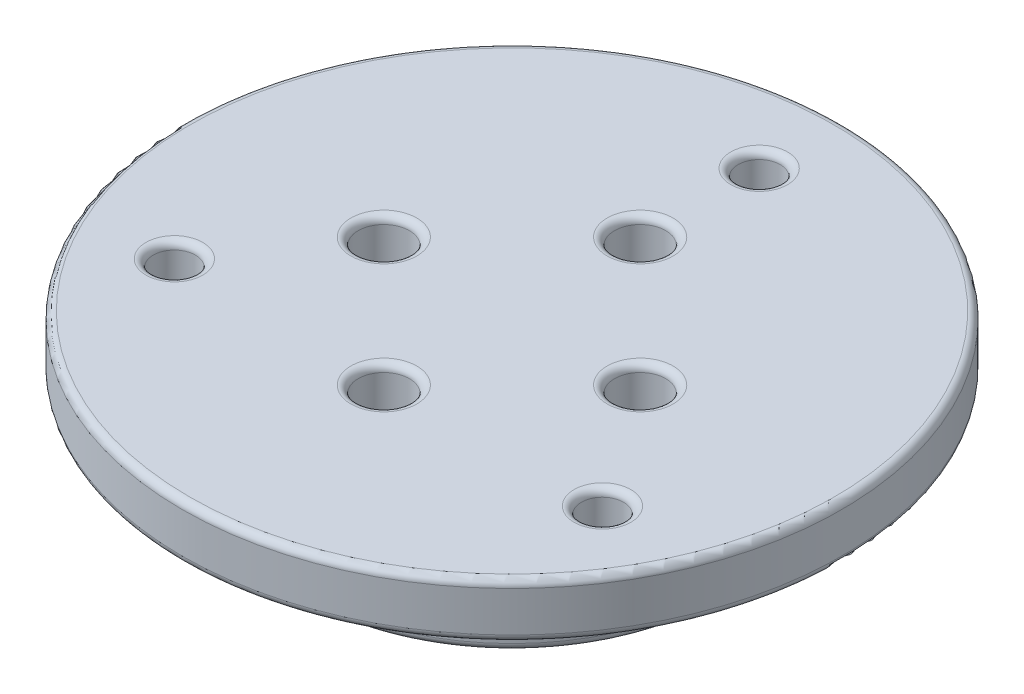
SolidWorks part; units mm, degrees
ref_plane "Front Plane" through (0, 0, 0) normal (0, 0, 1) x (1, 0, 0)
ref_plane "Top Plane" through (0, 0, 0) normal (0, 1, 0) x (1, 0, 0)
ref_plane "Right Plane" through (0, 0, 0) normal (1, 0, 0) x (0, 0, -1)
sketch "Sketch1" plane through (0, 0, 0) normal (0, 0, 1) x (1, 0, 0)
  line L0 (0, 0) -> (0, 8) construction
  line L1 (0, 0) -> (11.5, 0)
  line L4 (11.5, 0) -> (11.5, 5)
  line L5 (11.5, 5) -> (18, 5)
  line L6 (18, 5) -> (18, 8)
  line L7 (18, 8) -> (0, 8)
  line L8 (0, 0) -> (0, 8)
  dimension "D1" = 5
  dimension "D2" = 23
  dimension "D3" = 3
  dimension "D4" = 18
revolve "Revolve1" add sketch "Sketch1" angle 360 about L0
sketch "Sketch2" plane through (0, 8, 0) normal (0, 1, 0) x (1, 0, 0)
  line L0 (0, 13.5) -> (0, 0) construction
  circle A0 centre (0, 0) radius 13.5 construction
  circle A1 centre (0, 13.5) radius 1.15
  circle A2 centre (11.6913, -6.75) radius 1.15
  circle A3 centre (-11.6913, -6.75) radius 1.15
  circle A4 centre (0, 7) radius 1.4
  circle A5 centre (7, 0) radius 1.4
  circle A6 centre (0, -7) radius 1.4
  circle A7 centre (-7, 0) radius 1.4
  point P11 (0, 0)
  point P21 (0, 0)
  dimension "D1" = 2.3
  dimension "D2" = 27
  dimension "D4" = 7
  dimension "D5" = 2.8
  dimension "D3" = 3
  dimension "D6" = 4
extrude "Cut-Extrude1" cut sketch "Sketch2" against normal through all
fillet "Fillet2" radius 0.4 18 edges at (0, 0, -11.5) (7, 0, 1.4) (0, 0, -5.6) (0, 0, 8.4) (-7, 0, 1.4) (0, 5, -11.5) (0, 5, -18) (-11.6913, 5, 5.6) (11.6913, 5, 5.6) (0, 5, -14.65) (0, 8, -18) (7, 8, 1.4) (-11.6913, 8, 7.9) (11.6913, 8, 7.9) (0, 8, -5.6) (0, 8, 8.4) (-7, 8, 1.4) (0, 8, -12.35)
